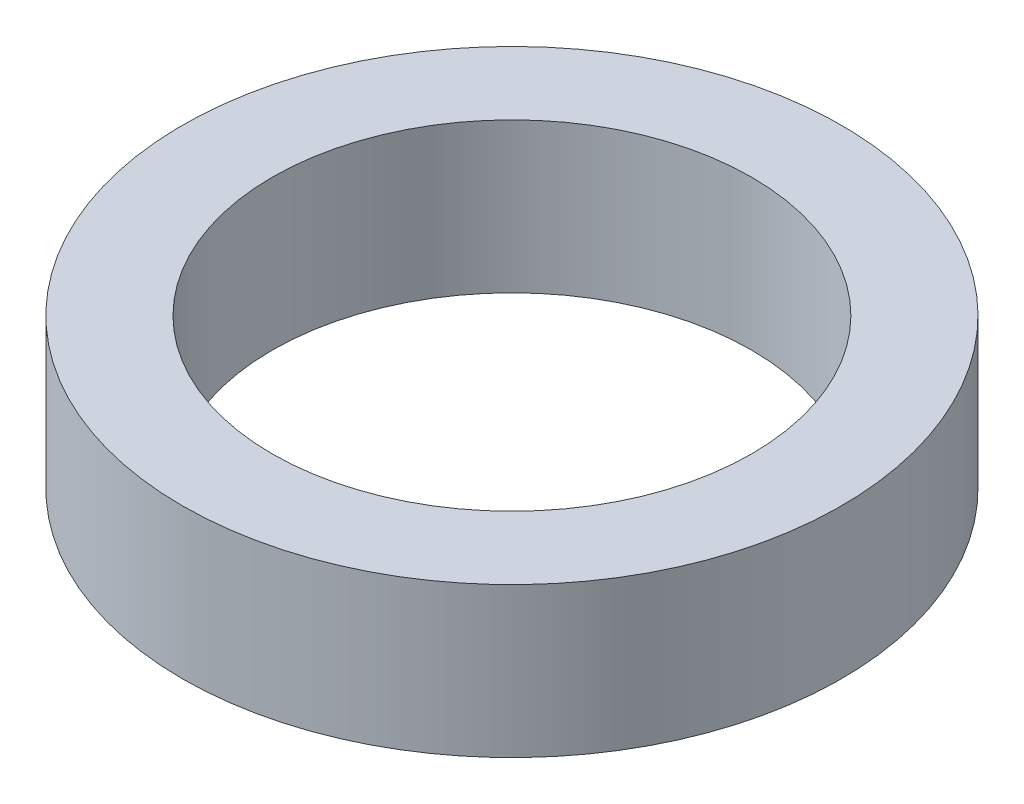
SolidWorks part; units mm, degrees
ref_plane "Front Plane" through (0, 0, 0) normal (0, 0, 1) x (1, 0, 0)
ref_plane "Top Plane" through (0, 0, 0) normal (0, 1, 0) x (1, 0, 0)
ref_plane "Right Plane" through (0, 0, 0) normal (1, 0, 0) x (0, 0, -1)
sketch "Sketch1" plane through (0, 0, 0) normal (0, 1, 0) x (1, 0, 0)
  circle A0 centre (0, 0) radius 8
  circle A1 centre (0, 0) radius 11
  dimension "D1" = 22
  dimension "D2" = 16
extrude "Boss-Extrude1" add sketch "Sketch1" along normal blind 5
